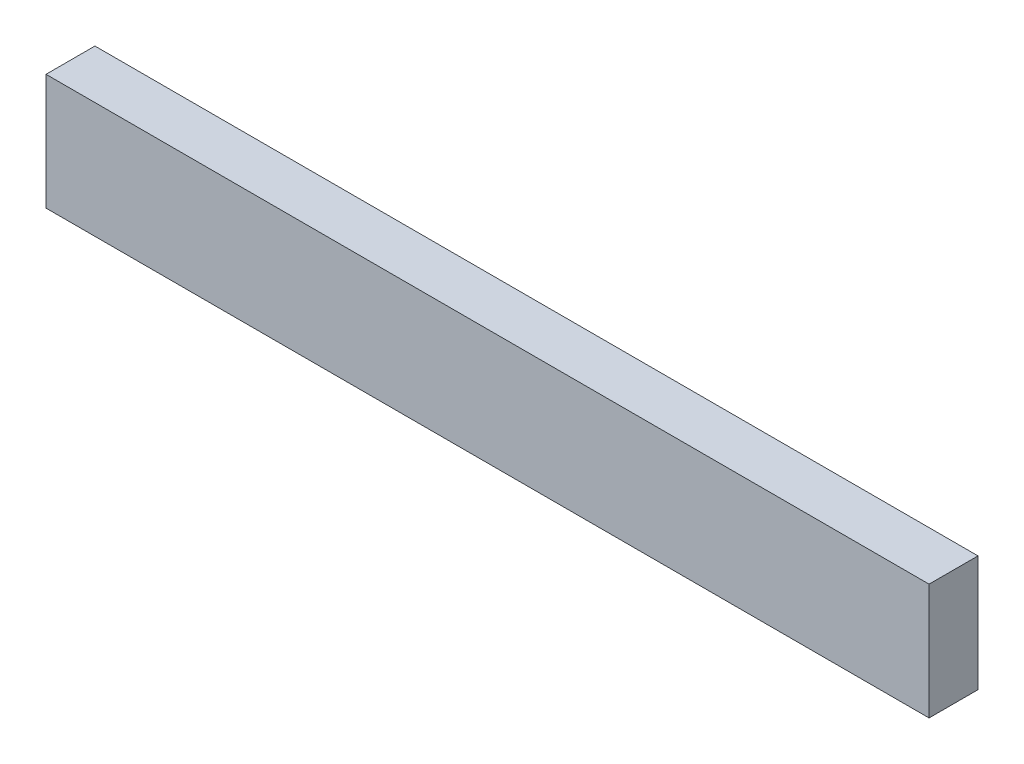
SolidWorks part; units mm, degrees
ref_plane "Front" through (0, 0, 0) normal (0, 0, 1) x (1, 0, 0)
ref_plane "Top" through (0, 0, 0) normal (0, 1, 0) x (1, 0, 0)
ref_plane "Right" through (0, 0, 0) normal (1, 0, 0) x (0, 0, -1)
sketch "Sketch1" plane through (0, 0, 0) normal (0, 1, 0) x (1, 0, 0)
  line L0 (342.85, 9) -> (342.85, -8.5) construction
  line L6 (342.85, 9.5) -> (0, 9.5)
  line L7 (342.85, 9.5) -> (342.85, -9.5)
  line L8 (342.85, -9.5) -> (0, -9.5)
  line L9 (0, 9.5) -> (0, -9.5)
  line L10 (342.85, 9.5) -> (0, -9.5) construction
  line L11 (342.85, -9.5) -> (0, 9.5) construction
  point P0 (171.425, 0)
  dimension "D1" = 19
extrude "Boss-Extrude1" add sketch "Sketch1" along normal blind 45
